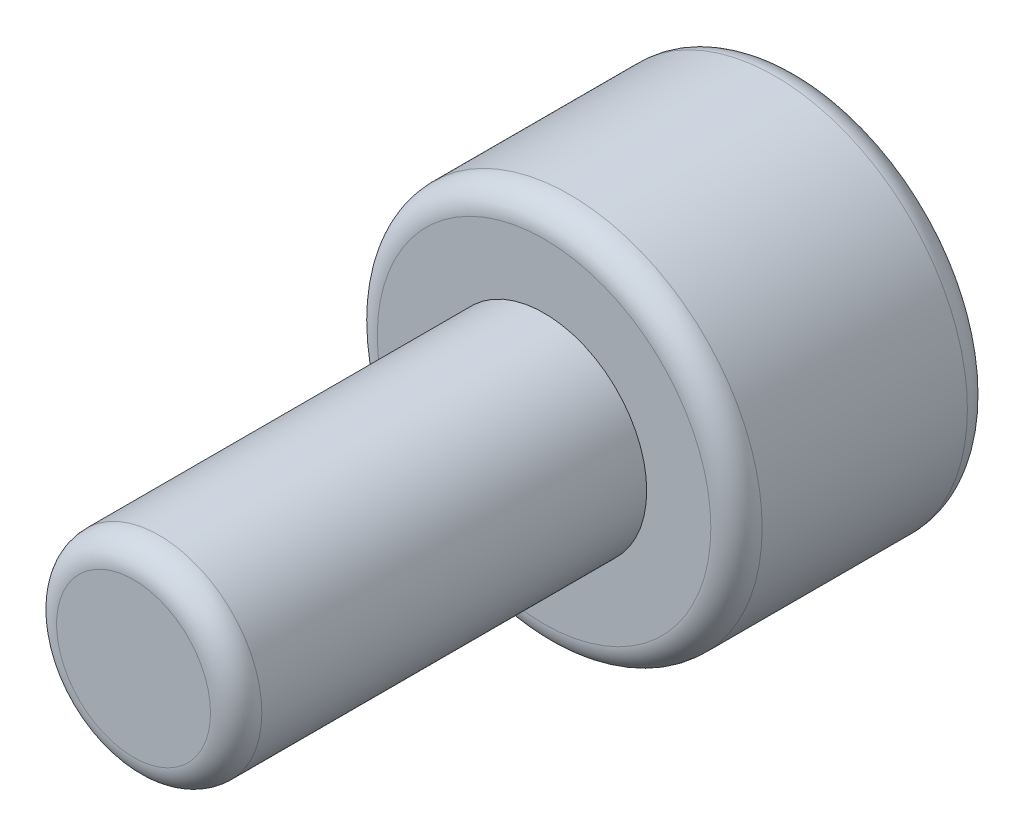
SolidWorks part; units mm, degrees
ref_plane "前视基准面" through (0, 0, 0) normal (0, 0, 1) x (1, 0, 0)
ref_plane "上视基准面" through (0, 0, 0) normal (0, 1, 0) x (1, 0, 0)
ref_plane "右视基准面" through (0, 0, 0) normal (1, 0, 0) x (0, 0, -1)
other "Configuration Table"
sketch "草图1" plane through (0, 0, 0) normal (0, 0, 1) x (1, 0, 0)
  circle A0 centre (0, 0) radius 2
  dimension "D1" = 4
extrude "凸台-拉伸1" add sketch "草图1" along normal blind 8
sketch "草图2" plane through (0, 0, 0) normal (0, 0, -1) x (-1, 0, 0)
  circle A0 centre (0, 0) radius 3.75
  dimension "D1" = 7.5
extrude "凸台-拉伸2" add sketch "草图2" along normal blind 5
sketch "草图4" plane through (0, 0, -5) normal (0, 0, -1) x (-1, 0, 0)
  line L0 (-1.4, 2.4249) -> (1.4, 2.4249)
  line L1 (1.4, 2.4249) -> (2.8, 0)
  line L2 (2.8, 0) -> (1.4, -2.4249)
  line L3 (1.4, -2.4249) -> (-1.4, -2.4249)
  line L4 (-1.4, -2.4249) -> (-2.8, 0)
  line L5 (-2.8, 0) -> (-1.4, 2.4249)
  circle A0 centre (0, 0) radius 3.75 construction
  point P0 (0, 0)
  point P3 (0, 0)
  point P5 (0, 2.4249)
  point P6 (-0.8471, 1.4393)
  point P19 (0, 0)
  dimension "D1" = 6
  dimension "D2" = 2.8
extrude "切除-拉伸2" cut sketch "草图4" against normal blind 3
fillet "圆角1" radius 0.5 9 edges at (2.8, 0, -3.5) (1.4, -2.4249, -3.5) (-1.4, -2.4249, -3.5) (-2.8, 0, -3.5) (1.4, 2.4249, -3.5) (-1.4, 2.4249, -3.5) (-3.75, 0, -5) (-3.75, 0, 0) (2, 0, 8)
